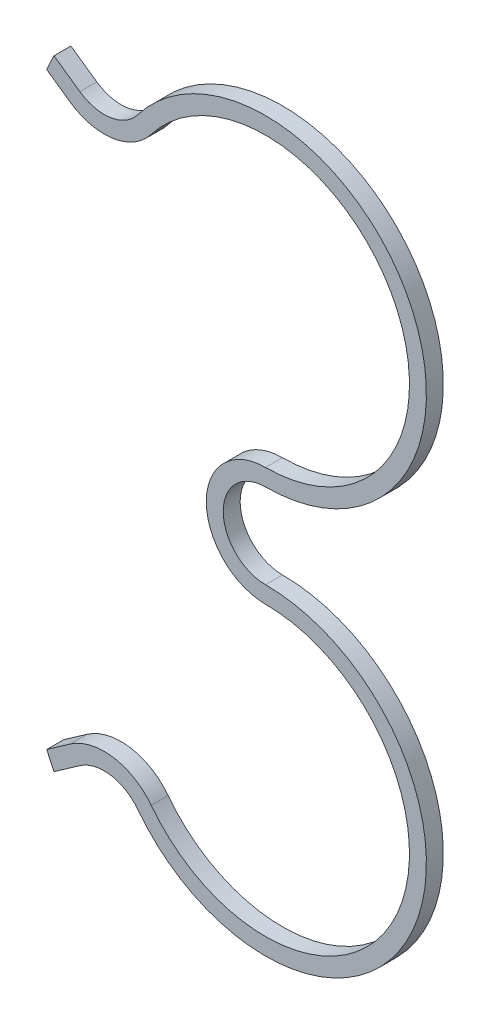
SolidWorks part; units mm, degrees
ref_plane "Plan de face" through (0, 0, 0) normal (0, 0, 1) x (1, 0, 0)
ref_plane "Plan de dessus" through (0, 0, 0) normal (0, 1, 0) x (1, 0, 0)
ref_plane "Plan de droite" through (0, 0, 0) normal (1, 0, 0) x (0, 0, -1)
sketch "Esquisse1" plane through (0, 0, 0) normal (0, 0, 1) x (1, 0, 0)
  line L8 (-12.9225, 17.3861) -> (-11.542, 16.4195)
  line L9 (-11.542, -16.4195) -> (-12.9225, -17.3861)
  line L10 (-11.4681, -20.0301) -> (-9.8213, -18.8769)
  line L11 (-9.8213, 18.8769) -> (-11.4681, 20.0301)
  arc A24 (-11.4681, 20.0301) -> (-12.9225, 17.3861) centre (0, 12) ccw
  arc A25 (-11.542, 16.4195) -> (-6.7536, 17.1613) centre (-9.5345, 19.2865) ccw
  arc A26 (0, 3.5) -> (-6.7536, 17.1613) centre (0, 12) ccw
  arc A27 (0, 3.5) -> (0, -3.5) centre (0, 0) ccw
  arc A28 (-6.7536, -17.1613) -> (0, -3.5) centre (0, -12) ccw
  arc A29 (-6.7536, -17.1613) -> (-11.542, -16.4195) centre (-9.5345, -19.2865) ccw
  arc A30 (-12.9225, -17.3861) -> (-11.4681, -20.0301) centre (0, -12) ccw
  arc A31 (-9.1372, -18.9829) -> (-9.8213, -18.8769) centre (-9.5345, -19.2865) ccw
  arc A32 (-9.1372, -18.9829) -> (0, -0.5) centre (0, -12) ccw
  arc A33 (0, 0.5) -> (0, -0.5) centre (0, 0) ccw
  arc A34 (0, 0.5) -> (-9.1372, 18.9829) centre (0, 12) ccw
  arc A35 (-9.8213, 18.8769) -> (-9.1372, 18.9829) centre (-9.5345, 19.2865) ccw
extrude "Boss.-Extru.2" add sketch "Esquisse1" along normal blind 1
sketch "Esquisse2" plane through (0, 0, 1) normal (0, 0, 1) x (1, 0, 0)
  line L2 (-12.9225, 17.3861) -> (-11.542, 16.4195)
  line L3 (-11.542, -16.4195) -> (-12.9225, -17.3861)
  line L4 (-10.9684, -17.2386) -> (-12.3489, -18.2052)
  line L5 (-12.3489, 18.2052) -> (-10.9684, 17.2386)
  line L6 (-10.9684, -17.2386) -> (-12.3489, -18.2052)
  line L7 (-12.3489, 18.2052) -> (-10.9684, 17.2386)
  line L8 (-12.9225, 17.3861) -> (-13.2956, 18.2052)
  line L9 (-12.3489, 18.2052) -> (-12.8989, 18.5904)
  line L10 (-12.8989, 18.5904) -> (-13.2956, 18.2052)
  line L11 (-12.3489, -18.2052) -> (-12.98, -18.6471)
  line L12 (-12.98, -18.6471) -> (-12.9225, -17.3861)
  arc A11 (-11.542, 16.4195) -> (-6.7536, 17.1613) centre (-9.5345, 19.2865) ccw
  arc A12 (0, 3.5) -> (-6.7536, 17.1613) centre (0, 12) ccw
  arc A13 (0, 3.5) -> (0, -3.5) centre (0, 0) ccw
  arc A14 (-6.7536, -17.1613) -> (0, -3.5) centre (0, -12) ccw
  arc A15 (-6.7536, -17.1613) -> (-11.542, -16.4195) centre (-9.5345, -19.2865) ccw
  arc A16 (-7.5481, -17.7685) -> (0, -2.5) centre (0, -12) ccw
  arc A17 (-7.5481, -17.7685) -> (-10.9684, -17.2386) centre (-9.5345, -19.2865) ccw
  arc A18 (0, 2.5) -> (0, -2.5) centre (0, 0) ccw
  arc A19 (0, 2.5) -> (-7.5481, 17.7685) centre (0, 12) ccw
  arc A20 (-10.9684, 17.2386) -> (-7.5481, 17.7685) centre (-9.5345, 19.2865) ccw
  arc A21 (-7.5481, -17.7685) -> (0, -2.5) centre (0, -12) ccw
  arc A22 (-7.5481, -17.7685) -> (-10.9684, -17.2386) centre (-9.5345, -19.2865) ccw
  arc A23 (0, 2.5) -> (0, -2.5) centre (0, 0) ccw
  arc A24 (0, 2.5) -> (-7.5481, 17.7685) centre (0, 12) ccw
  arc A25 (-10.9684, 17.2386) -> (-7.5481, 17.7685) centre (-9.5345, 19.2865) ccw
  dimension "D1" = 1
  dimension "D2" = 1
extrude "Enlèv. mat.-Extru.1" cut sketch "Esquisse2" against normal through all flip side to cut
